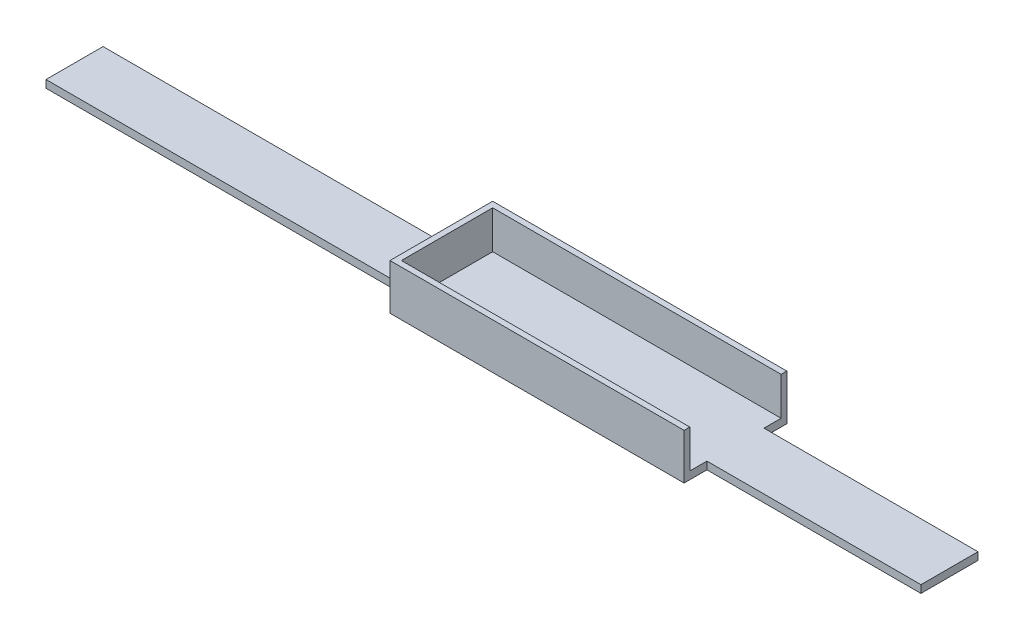
SolidWorks part; units mm, degrees
material "ABS"
ref_plane "Alzado" through (0, 0, 0) normal (0, 0, 1) x (1, 0, 0)
ref_plane "Planta" through (0, 0, 0) normal (0, 1, 0) x (1, 0, 0)
ref_plane "Vista lateral" through (0, 0, 0) normal (1, 0, 0) x (0, 0, -1)
sketch "Croquis1" plane through (0, 0, 0) normal (0, 1, 0) x (1, 0, 0)
  line L1 (-115, 12.2478) -> (115, 12.2478)
  line L2 (-115, 12.2478) -> (-115, -2.7522)
  line L3 (-115, -2.7522) -> (115, -2.7522)
  line L4 (115, 12.2478) -> (115, -2.7522)
  point P0 (0, 0)
  dimension "D1" = 230
  dimension "D2" = 15
extrude "Saliente-Extruir1" add sketch "Croquis1" along normal blind 2
sketch "Croquis2" plane through (115, 0, 0) normal (1, 0, 0) x (0, 0, -1)
  line L0 (12.2478, 2) -> (12.2478, 0) construction
  line L9 (-17.7522, 12) -> (27.2478, 12)
  line L10 (-17.7522, 12) -> (-17.7522, -10)
  line L11 (-17.7522, -10) -> (27.2478, -10)
  line L12 (27.2478, 12) -> (27.2478, -10)
  line L13 (-2.7522, 2) -> (-2.7522, 0) construction
  line L14 (-2.7522, 2) -> (12.2478, 2) construction
  line L15 (-2.7522, 0) -> (12.2478, 0) construction
  dimension "D1" = 15
  dimension "D2" = 15
  dimension "D3" = 10
  dimension "D4" = 10
extrude "Saliente-Extruir2" add sketch "Croquis2" along normal blind 5
sketch "Croquis3" plane through (-115, 0, 0) normal (-1, 0, 0) x (0, 0, 1)
  line L9 (-27.2478, 12) -> (17.7522, 12)
  line L10 (-27.2478, 12) -> (-27.2478, -10)
  line L11 (-27.2478, -10) -> (17.7522, -10)
  line L12 (17.7522, 12) -> (17.7522, -10)
extrude "Saliente-Extruir3" add sketch "Croquis3" along normal blind 5
sketch "Croquis4" plane through (0, 2, 0) normal (0, 1, 0) x (1, 0, 0)
  line L0 (-115, 20.9446) -> (115, 20.9446) construction
  line L1 (-115, -17.7522) -> (-115, 27.2478) construction
  line L2 (115, 27.2478) -> (115, -17.7522) construction
sketch "Croquis5" plane through (0, 2, 0) normal (0, 1, 0) x (1, 0, 0)
  line L0 (115, 12.2478) -> (-115, 12.2478) construction
  line L1 (115, -2.7522) -> (115, 12.2478) construction
  circle A0 centre (0, 4.7478) radius 2.3844 construction
  point P5 (0, 12.2478)
  point P8 (115, 4.7478)
sketch "Croquis6" plane through (0, 0, -12.2478) normal (0, 0, -1) x (-1, 0, 0)
  line L0 (18.5824, 2) -> (18.5824, 0)
  line L1 (115, 2) -> (-115, 2) construction
  line L2 (-115, 0) -> (115, 0) construction
  line L3 (18.5824, 0) -> (-58.7427, 0)
  line L4 (-58.7427, 0) -> (-58.7427, 2)
  line L5 (-58.7427, 2) -> (18.5824, 2)
extrude "Saliente-Extruir4" add sketch "Croquis6" along normal blind 6 and the other way offset from surface (21 mm away) 6 other way up to face at (0, 1, 2.7522)
sketch "Croquis7" plane through (0, 2, 0) normal (0, 1, 0) x (1, 0, 0)
  line L0 (-18.5824, 18.2478) -> (-18.5824, -8.7522)
  line L1 (-18.5824, -8.7522) -> (58.7427, -8.7522)
  line L2 (58.7427, -8.7522) -> (58.7427, -7.2522)
  line L3 (58.7427, -8.7522) -> (58.7427, -2.7522) construction
  line L4 (58.7427, -7.2522) -> (-17.0824, -7.2522)
  line L5 (-17.0824, -7.2522) -> (-17.0824, 16.7478)
  line L6 (-17.0824, 16.7478) -> (58.7427, 16.7478)
  line L7 (58.7427, 12.2478) -> (58.7427, 18.2478) construction
  line L8 (58.7427, 16.7478) -> (58.7427, 18.2478)
  line L9 (58.7427, 18.2478) -> (-18.5824, 18.2478)
  dimension "D1" = 1.5
  dimension "D2" = 1.5
  dimension "D3" = 1.5
extrude "Saliente-Extruir5" add sketch "Croquis7" along normal blind 10
sketch "Croquis8" plane through (0, 2, 0) normal (0, 1, 0) x (1, 0, 0)
  line L0 (-115, -17.7522) -> (-115, 27.2478) construction
  line L1 (-70, 6.7478) -> (-67, 6.7478)
  line L2 (-70, 6.7478) -> (-70, 2.7478)
  line L3 (-70, 2.7478) -> (-67, 2.7478)
  line L4 (-67, 6.7478) -> (-67, 2.7478)
  line L5 (67, 6.7478) -> (70, 6.7478)
  line L6 (67, 6.7478) -> (67, 2.7478)
  line L7 (67, 2.7478) -> (70, 2.7478)
  line L8 (70, 6.7478) -> (70, 2.7478)
  line L9 (115, 27.2478) -> (115, -17.7522) construction
  point P12 (-115, 4.7478)
  point P13 (-70, 4.7478)
  point P14 (115, 4.7478)
  point P15 (70, 4.7478)
  dimension "D1" = 45
  dimension "D2" = 45
  dimension "D3" = 3
  dimension "D4" = 3
  dimension "D5" = 4
  dimension "D6" = 4
sketch "Croquis9" plane through (0, 0, 17.7522) normal (0, 0, 1) x (1, 0, 0)
  line L0 (-120, -10) -> (-120, 12) construction
  line L1 (-120, 12) -> (-115, 12)
  line L2 (-120, 12) -> (-120, -10)
  line L3 (-120, -10) -> (-115, -10)
  line L4 (-115, 12) -> (-115, -10)
  line L6 (115, 12) -> (120, 12)
  line L7 (115, 12) -> (115, -10)
  line L8 (115, -10) -> (120, -10)
  line L9 (120, 12) -> (120, -10)
extrude "Cortar-Extruir1" cut sketch "Croquis9" against normal up to next
